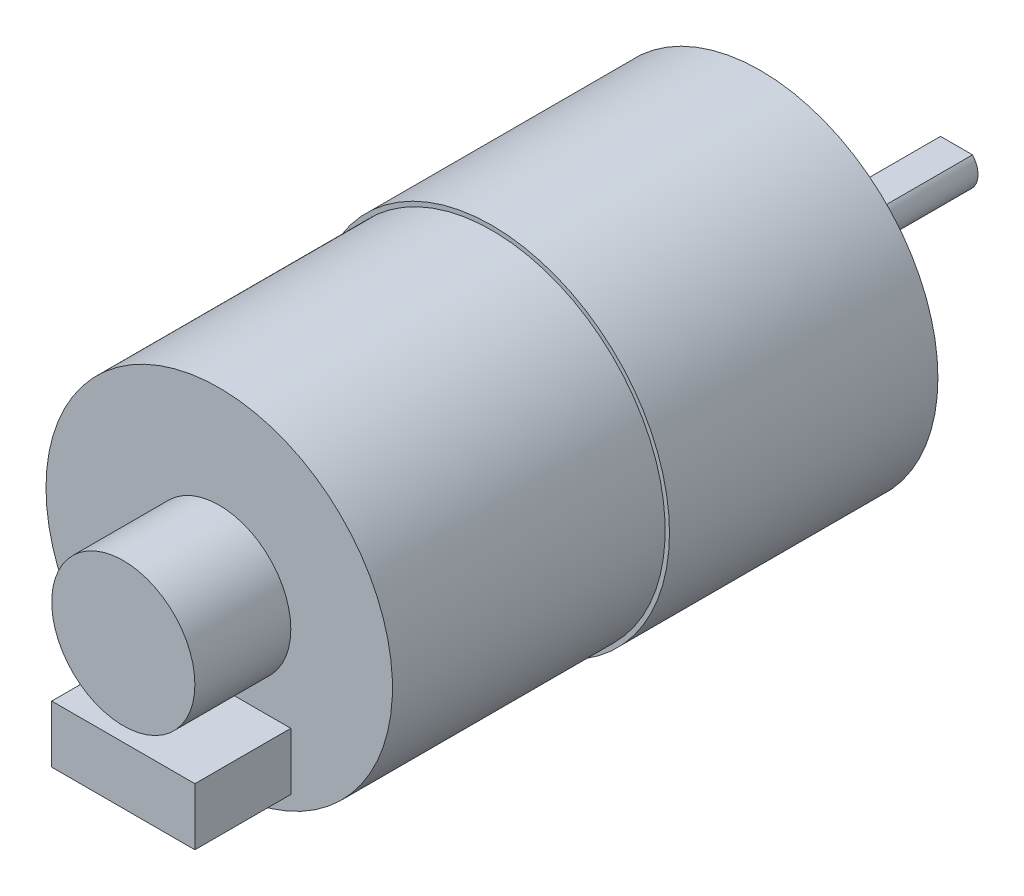
SolidWorks part; units mm, degrees
ref_plane "前视基准面" through (0, 0, 0) normal (0, 0, 1) x (1, 0, 0)
ref_plane "上视基准面" through (0, 0, 0) normal (0, 1, 0) x (1, 0, 0)
ref_plane "右视基准面" through (0, 0, 0) normal (1, 0, 0) x (0, 0, -1)
sketch "草图1" plane through (0, 0, 0) normal (0, 0, 1) x (1, 0, 0)
  circle A0 centre (0, 0) radius 12.4
  dimension "D1" = 24.8
extrude "凸台-拉伸1" add sketch "草图1" along normal blind 18.75
sketch "草图2" plane through (0, 0, 18.75) normal (0, 0, 1) x (1, 0, 0)
  circle A0 centre (0, 0) radius 12.1
  dimension "D1" = 24.2
extrude "凸台-拉伸2" add sketch "草图2" along normal blind 19.05
sketch "草图3" plane through (0, 0, 0) normal (0, 0, -1) x (-1, 0, 0)
  circle A0 centre (0, 0) radius 3.5
  dimension "D1" = 7
extrude "凸台-拉伸3" add sketch "草图3" along normal blind 2.7
sketch "草图4" plane through (0, 0, -2.7) normal (0, 0, -1) x (-1, 0, 0)
  circle A0 centre (0, 0) radius 1.5
  dimension "D1" = 3
extrude "凸台-拉伸4" add sketch "草图4" along normal blind 11
sketch "草图5" plane through (0, 0, -13.7) normal (0, 0, -1) x (-1, 0, 0)
  line L1 (-1.5706, 2.7169) -> (2.1741, 2.7169)
  line L2 (-1.5706, 2.7169) -> (-1.5706, 1)
  line L3 (-1.5706, 1) -> (2.1741, 1)
  line L4 (2.1741, 2.7169) -> (2.1741, 1)
  circle A0 centre (0, 0) radius 1.5 construction
  dimension "D1" = 1
extrude "切除-拉伸1" cut sketch "草图5" against normal blind 8
sketch "草图6" plane through (0, 0, 37.8) normal (0, 0, 1) x (1, 0, 0)
  circle A0 centre (0, 0) radius 5
  dimension "D1" = 10
extrude "凸台-拉伸5" add sketch "草图6" along normal blind 6.7
sketch "草图7" plane through (0, 0, 44.5) normal (0, 0, 1) x (1, 0, 0)
  line L1 (-5, -6) -> (5, -6)
  line L2 (-5, -6) -> (-5, -10)
  line L3 (-5, -10) -> (5, -10)
  line L4 (5, -6) -> (5, -10)
  line L5 (-5, -6) -> (5, -10) construction
  line L6 (-5, -10) -> (5, -6) construction
  point P0 (0, -8)
  point P5 (0, 0)
  dimension "D1" = 10
  dimension "D2" = 4
  dimension "D3" = 6
extrude "凸台-拉伸6" add sketch "草图7" against normal blind 16.7 separate body
sketch "草图8" plane through (0, 0, 0) normal (0, 0, -1) x (-1, 0, 0)
  circle A0 centre (0, 0) radius 8.5
  point P3 (-8.5, 0)
  point P4 (8.5, 0)
  dimension "D1" = 17
hole_wizard "M3 螺纹孔1" positions "3D草图1" profile "草图9" tap size "M3" standard "GB"
sketch3d "3D草图1"
  point P0 (-8.5, 0, 0)
  point P3 (8.5, 0, 0)
sketch "草图9" plane through (-8.5, 0, 0) normal (1, 0, 0) x (0, 1, 0)
  line L0 (0, 0) -> (0, 5)
  line L1 (0, 5) -> (1.25, 4.2489)
  line L2 (1.25, 4.2489) -> (1.25, 0)
  line L5 (1.25, 0) -> (0, 0)
  line L10 (0, 5) -> (-1.25, 4.2489) construction
  line L11 (0, -6.35) -> (0, 107.95) construction
  dimension "螺纹孔钻头直径" = 2.5
  dimension "螺纹孔钻头深度" = 5
  dimension "导头角度" = 118
cosmetic thread "孔螺蚊线1" parameters "D1"=4.2489, "D2"=3
cosmetic thread "孔螺蚊线2" parameters "D1"=4.2489, "D2"=3
